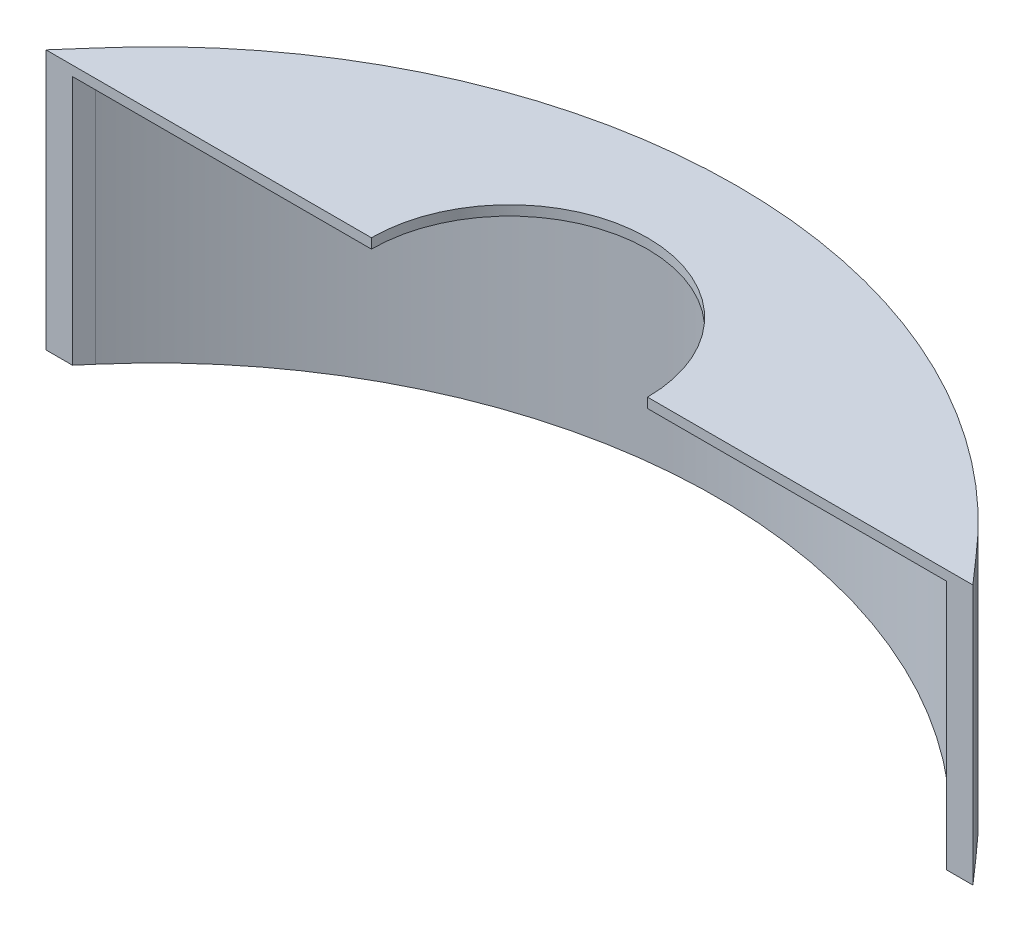
SolidWorks part; units mm, degrees
ref_plane "Front Plane" through (0, 0, 0) normal (0, 0, 1) x (1, 0, 0)
ref_plane "Top Plane" through (0, 0, 0) normal (0, 1, 0) x (1, 0, 0)
ref_plane "Right Plane" through (0, 0, 0) normal (1, 0, 0) x (0, 0, -1)
sketch "Sketch1" plane through (0, 0, 0) normal (0, 1, 0) x (1, 0, 0)
  line L0 (-113.7728, 5.431) -> (121.2361, 5.431) construction
  line L1 (-106.2684, 10.1773) -> (113.7316, 10.1773) construction
  line L2 (-106.2684, 10.1773) -> (-113.7728, 5.431) construction
  line L3 (113.7316, 10.1773) -> (121.2361, 5.431) construction
  line L4 (-113.7728, 5.431) -> (-113.7728, -50.0431) construction
  line L5 (121.2361, 5.431) -> (121.2361, -44.612) construction
  line L6 (-106.2684, 10.1773) -> (3.7316, -84.3835) construction
  line L7 (3.7316, -84.3835) -> (113.7316, 10.1773) construction
  line L8 (-108.1642, 11.807) -> (-113.7728, 5.431)
  line L9 (115.6274, 11.807) -> (121.2361, 5.431)
  line L10 (-106.2684, 10.1773) -> (-110.4434, 5.431)
  line L11 (113.7316, 10.1773) -> (117.9067, 5.431)
  line L12 (117.9067, 5.431) -> (121.2361, 5.431)
  line L13 (-113.7728, 5.431) -> (-110.4434, 5.431)
  arc A0 (-106.2684, 10.1773) -> (113.7316, 10.1773) centre (3.7316, -84.3835) cw
  arc A1 (-108.1642, 11.807) -> (115.6274, 11.807) centre (3.7316, -84.3835) cw
  point P10 (118.753, 5.431)
  dimension "D2" = 220
  dimension "D1" = 235.0089
  dimension "D3" = 221.337
  dimension "D4" = 98.632
  dimension "D5" = 2.5
extrude "Boss-Extrude1" add sketch "Sketch1" along normal blind 63.4
sketch "Sketch2" plane through (0, 63.4, 0) normal (0, 1, 0) x (1, 0, 0)
  line L0 (-113.7728, 5.431) -> (121.2361, 5.431)
  line L1 (121.2361, 5.431) -> (115.6274, 11.807)
  line L2 (-113.7728, 5.431) -> (-108.1642, 11.807)
  arc A0 (-108.1642, 11.807) -> (115.6274, 11.807) centre (3.7316, -84.3835) cw
extrude "Boss-Extrude2" add sketch "Sketch2" along normal blind 2.5
sketch "Sketch3" plane through (0, 0, 0) normal (0, 1, 0) x (1, 0, 0)
  line L0 (-110.4434, 5.431) -> (-106.2684, 10.1773)
  line L1 (117.9067, 5.431) -> (113.7316, 10.1773)
  line L2 (-104.3726, 8.5476) -> (-107.0517, 5.431)
  line L3 (-107.0517, 5.431) -> (-110.4434, 5.431)
  line L4 (111.8358, 8.5476) -> (114.515, 5.431)
  line L5 (114.515, 5.431) -> (117.9067, 5.431)
  arc A0 (-106.2684, 10.1773) -> (113.7316, 10.1773) centre (3.7316, -84.3835) cw
  arc A1 (-104.3726, 8.5476) -> (111.8358, 8.5476) centre (3.7316, -84.3835) cw
  point P2 (0, 0)
  point P12 (0, 0)
  dimension "D1" = 2.5
extrude "Boss-Extrude3" add sketch "Sketch3" along normal up to surface (63.4 mm away) contours A1 L4 L5 L1 A0 L0 L3 L2 up to face at (3.7316, 63.4, -20.4284)
sketch "Sketch4" plane through (0, 65.9, 0) normal (0, 1, 0) x (1, 0, 0)
  line L0 (-113.7728, 5.431) -> (121.2361, 5.431) construction
  circle A0 centre (3.7316, 5.431) radius 35
extrude "Cut-Extrude1" cut sketch "Sketch4" against normal through all
